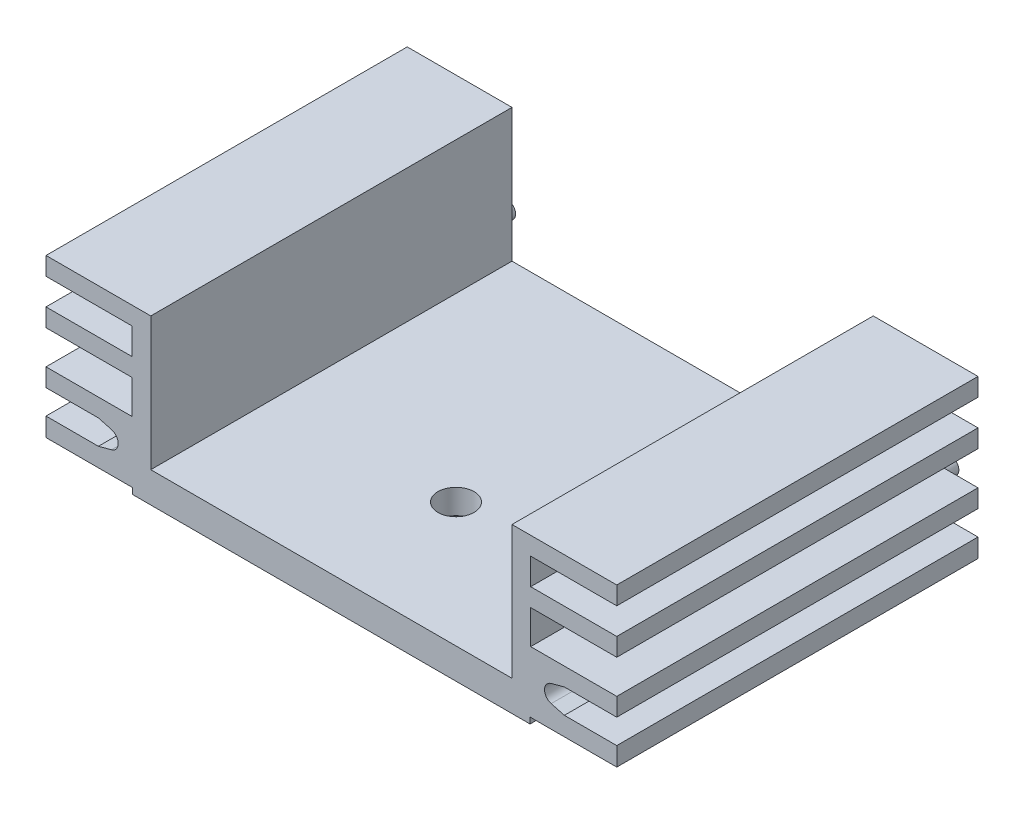
SolidWorks part; units mm, degrees
ref_plane "Front Plane" through (0, 0, 0) normal (0, 0, 1) x (1, 0, 0)
ref_plane "Top Plane" through (0, 0, 0) normal (0, 1, 0) x (1, 0, 0)
ref_plane "Right Plane" through (0, 0, 0) normal (1, 0, 0) x (0, 0, -1)
sketch "Sketch1" plane through (0, 0, 0) normal (0, 0, 1) x (1, 0, 0)
  line L0 (0, 24.3033) -> (0, -14.3062) construction
  line L1 (-15, 13.1) -> (-15, 2.04)
  line L2 (-15, 2.04) -> (15, 2.04)
  line L3 (-15, 13.1) -> (-23.7, 13.1)
  line L4 (-23.7, 13.1) -> (-23.7, 11.6)
  line L5 (-23.7, 11.6) -> (-16.55, 11.6)
  line L6 (16.5, -0.5) -> (-16.5, -0.5)
  line L7 (-16.5, -0.5) -> (-16.5, 0)
  line L8 (-16.5, 0) -> (-23.7, 0)
  line L9 (-23.7, 0) -> (-23.7, 1.55)
  line L10 (-23.7, 9.4) -> (-23.7, 7.9)
  line L11 (-23.7, 7.9) -> (-16.55, 7.9)
  line L12 (-23.7, 9.4) -> (-16.55, 9.4)
  line L13 (-16.55, 9.4) -> (-16.55, 11.6)
  line L14 (-23.7, 1.55) -> (-19.35, 1.55)
  line L15 (-19.35, 1.55) -> (-18.2544, 1.846)
  line L16 (-19.35, 3.59) -> (-23.7, 3.59)
  line L17 (-16.55, 7.9) -> (-16.55, 5.09)
  line L18 (-16.55, 5.09) -> (-23.7, 5.09)
  line L19 (-23.7, 5.09) -> (-23.7, 3.59)
  line L20 (-18.2544, 3.294) -> (-19.35, 3.59)
  line L21 (-23.7, 3.59) -> (-23.7, 1.55) construction
  line L22 (-23.7, 2.57) -> (-16.1511, 2.57) construction
  line L23 (23.7, 2.57) -> (16.1511, 2.57) construction
  line L24 (23.7, 3.59) -> (23.7, 1.55) construction
  line L25 (18.2544, 3.294) -> (19.35, 3.59)
  line L26 (23.7, 5.09) -> (23.7, 3.59)
  line L27 (16.55, 5.09) -> (23.7, 5.09)
  line L28 (16.55, 7.9) -> (16.55, 5.09)
  line L29 (19.35, 3.59) -> (23.7, 3.59)
  line L30 (19.35, 1.55) -> (18.2544, 1.846)
  line L31 (23.7, 1.55) -> (19.35, 1.55)
  line L32 (16.55, 9.4) -> (16.55, 11.6)
  line L33 (23.7, 9.4) -> (16.55, 9.4)
  line L34 (23.7, 7.9) -> (16.55, 7.9)
  line L35 (23.7, 9.4) -> (23.7, 7.9)
  line L36 (23.7, 0) -> (23.7, 1.55)
  line L37 (16.5, 0) -> (23.7, 0)
  line L38 (16.5, -0.5) -> (16.5, 0)
  line L39 (23.7, 11.6) -> (16.55, 11.6)
  line L40 (23.7, 13.1) -> (23.7, 11.6)
  line L41 (15, 13.1) -> (23.7, 13.1)
  line L42 (15, 13.1) -> (15, 2.04)
  arc A0 (-18.2544, 1.846) -> (-18.2544, 3.294) centre (-18.45, 2.57) ccw
  arc A1 (18.2544, 1.846) -> (18.2544, 3.294) centre (18.45, 2.57) cw
  point P47 (0, -0.5)
  point P51 (0, 2.04)
  dimension "D12" = 4.35
  dimension "D13" = 0.75
  dimension "D1" = 47.4
  dimension "D2" = 30
  dimension "D3" = 13.1
  dimension "D4" = 1.5
  dimension "D5" = 7.15
  dimension "D7" = 2.2
  dimension "D8" = 2.54
  dimension "D9" = 0.5
  dimension "D10" = 33
  dimension "D11" = 1.55
  dimension "D14" = 2.04
  dimension "D15" = 5.25
  dimension "D6" = 2
extrude "Boss-Extrude1" add sketch "Sketch1" along normal mid plane 30
sketch "Sketch2" plane through (0, -0.5, 0) normal (0, -1, 0) x (1, 0, 0)
  line L0 (-16.5, 15) -> (16.5, 15) construction
  circle A0 centre (0, 4.65) radius 1.5
  dimension "D1" = 10.35
  dimension "D2" = 3
extrude "Cut-Extrude1" cut sketch "Sketch2" against normal through all
chamfer "Chamfer1" distance 0.5 angle 45 1 edges at (0, -0.5, 3.15)
sketch "Sketch3" plane through (0, 0, -15) normal (0, 0, -1) x (-1, 0, 0)
  line L0 (-17.7, 2.57) -> (17.7, 2.57) construction
  line L1 (0, 0) -> (0, 10.9541) construction
  arc A0 (-18.2544, 1.846) -> (-18.2544, 3.294) centre (-18.45, 2.57) ccw construction
  arc A1 (18.2544, 3.294) -> (18.2544, 1.846) centre (18.45, 2.57) ccw construction
  circle A2 centre (-18.405, 2.57) radius 0.705
  circle A3 centre (18.405, 2.57) radius 0.705
  point P13 (0, 0)
  dimension "D1" = 1.41
extrude "Boss-Extrude2" add sketch "Sketch3" along normal blind 3 and the other way blind 7 separate body
